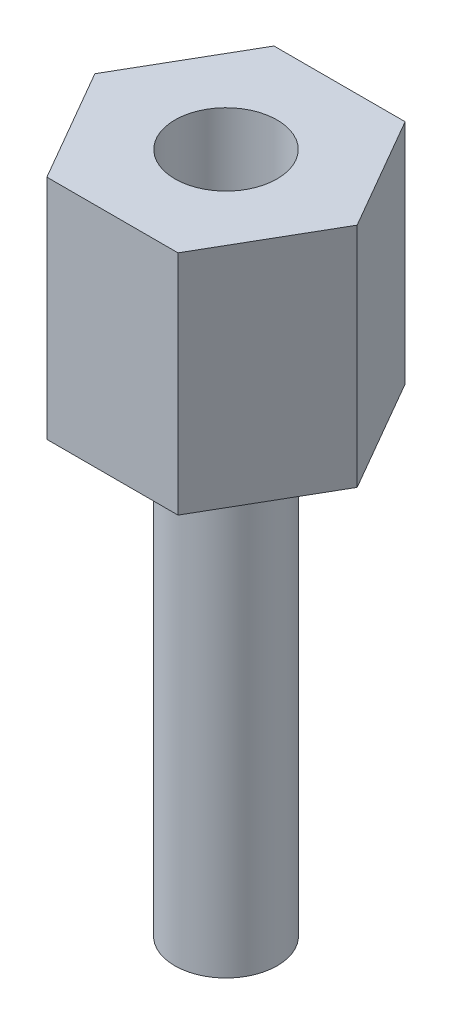
SolidWorks part; units mm, degrees
ref_plane "Front Plane" through (0, 0, 0) normal (0, 0, 1) x (1, 0, 0)
ref_plane "Top Plane" through (0, 0, 0) normal (0, 1, 0) x (1, 0, 0)
ref_plane "Right Plane" through (0, 0, 0) normal (1, 0, 0) x (0, 0, -1)
sketch "Esquisse1" plane through (0, 0, 0) normal (0, 1, 0) x (1, 0, 0)
  line L1 (3.4641, 0) -> (1.7321, 3)
  line L2 (1.7321, 3) -> (-1.7321, 3)
  line L3 (-1.7321, 3) -> (-3.4641, 0)
  line L4 (-3.4641, 0) -> (-1.7321, -3)
  line L5 (-1.7321, -3) -> (1.7321, -3)
  line L6 (1.7321, -3) -> (3.4641, 0)
  circle A0 centre (0, 0) radius 3 construction
extrude "Boss.-Extru.1" add sketch "Esquisse1" along normal blind 6
sketch "Esquisse2" plane through (0, 0, 0) normal (0, -1, 0) x (1, 0, 0)
  circle A0 centre (0, 0) radius 1.3538
extrude "Boss.-Extru.2" add sketch "Esquisse2" along normal blind 12
sketch "Esquisse3" plane through (0, 6, 0) normal (0, 1, 0) x (1, 0, 0)
  circle A0 centre (0, 0) radius 1.35
extrude "Enlèv. mat.-Extru.1" cut sketch "Esquisse3" against normal blind 5
